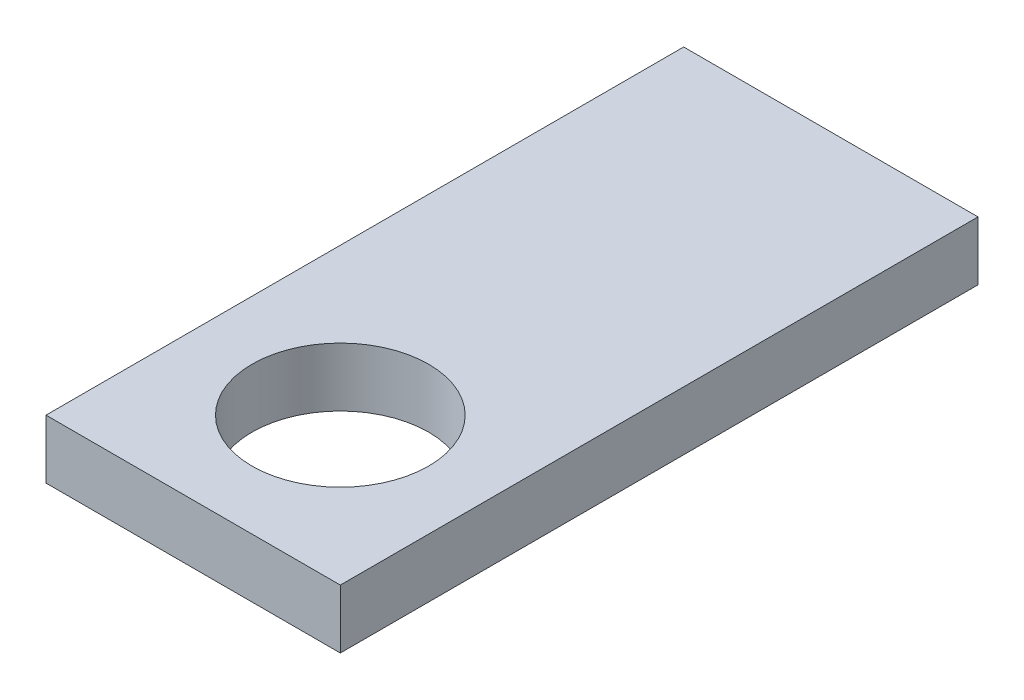
SolidWorks part; units mm, degrees
ref_plane "前视基准面" through (0, 0, 0) normal (0, 0, 1) x (1, 0, 0)
ref_plane "上视基准面" through (0, 0, 0) normal (0, 1, 0) x (1, 0, 0)
ref_plane "右视基准面" through (0, 0, 0) normal (1, 0, 0) x (0, 0, -1)
other "Configuration Table"
sketch "草图1" plane through (0, 0, 0) normal (0, 1, 0) x (1, 0, 0)
  line L0 (0, 0) -> (0, 25)
  line L1 (-7.5, -7.5) -> (7.5, -7.5)
  line L2 (-7.5, -7.5) -> (-7.5, 7.5)
  line L3 (-7.5, 7.5) -> (7.5, 7.5)
  line L4 (7.5, -7.5) -> (7.5, 7.5)
  line L5 (-7.5, -7.5) -> (7.5, 7.5) construction
  line L6 (-7.5, 7.5) -> (7.5, -7.5) construction
  line L8 (-7.5, 7.5) -> (7.5, 7.5)
  line L9 (-7.5, 7.5) -> (-7.5, 25)
  line L10 (-7.5, 25) -> (7.5, 25)
  line L11 (7.5, 7.5) -> (7.5, 25)
  circle A0 centre (0, 0) radius 4.5
  dimension "D1" = 9
  dimension "D2" = 15
  dimension "D3" = 15
  dimension "D4" = 25
extrude "凸台-拉伸2" add sketch "草图1" along normal blind 3
